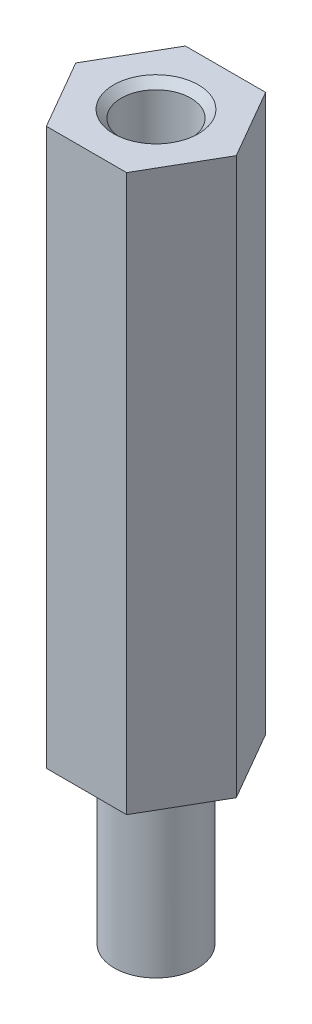
SolidWorks part; units mm, degrees
ref_plane "Front Plane" through (0, 0, 0) normal (0, 0, 1) x (1, 0, 0)
ref_plane "Top Plane" through (0, 0, 0) normal (0, 1, 0) x (1, 0, 0)
ref_plane "Right Plane" through (0, 0, 0) normal (1, 0, 0) x (0, 0, -1)
sketch "Sketch1" plane through (0, 0, 0) normal (0, 1, 0) x (1, 0, 0)
  line L1 (2.8868, 0) -> (1.4434, 2.5)
  line L2 (1.4434, 2.5) -> (-1.4434, 2.5)
  line L3 (-1.4434, 2.5) -> (-2.8868, 0)
  line L4 (-2.8868, 0) -> (-1.4434, -2.5)
  line L5 (-1.4434, -2.5) -> (1.4434, -2.5)
  line L6 (1.4434, -2.5) -> (2.8868, 0)
  circle A0 centre (0, 0) radius 2.5 construction
extrude "Boss-Extrude1" add sketch "Sketch1" along normal blind 20
hole_wizard "M3x0.5 Tapped Hole1" positions "Sketch3" profile "Sketch2" tap size "M3x0.5" standard "ANSI Metric"
sketch "Sketch3" plane through (0, 20, 0) normal (0, 1, 0) x (1, 0, 0)
  point P0 (0, 0)
sketch "Sketch2" plane through (0, 20, 0) normal (1, 0, 0) x (0, 0, 1)
  line L0 (0, 0) -> (0, 9.2511)
  line L1 (0, 9.2511) -> (1.25, 8.5)
  line L2 (1.25, 8.5) -> (1.25, 0.275)
  line L3 (1.25, 0.275) -> (1.525, 0)
  line L5 (1.525, 0) -> (0, 0)
  line L6 (-1.25, 0.275) -> (-1.525, 0) construction
  line L10 (0, 9.2511) -> (-1.25, 8.5) construction
  line L11 (0, -6.35) -> (0, 107.95) construction
  dimension "Tap Drill Dia." = 2.5
  dimension "Tap Drill Depth" = 8.5
  dimension "Near C'Sink Dia." = 3.05
  dimension "Near C'Sink Angle" = 90
  dimension "Drill Angle" = 118
sketch "Sketch4" plane through (0, 0, 0) normal (0, -1, 0) x (1, 0, 0)
  circle A0 centre (0, 0) radius 1.5
  dimension "D1" = 3
extrude "Boss-Extrude2" add sketch "Sketch4" along normal blind 6
